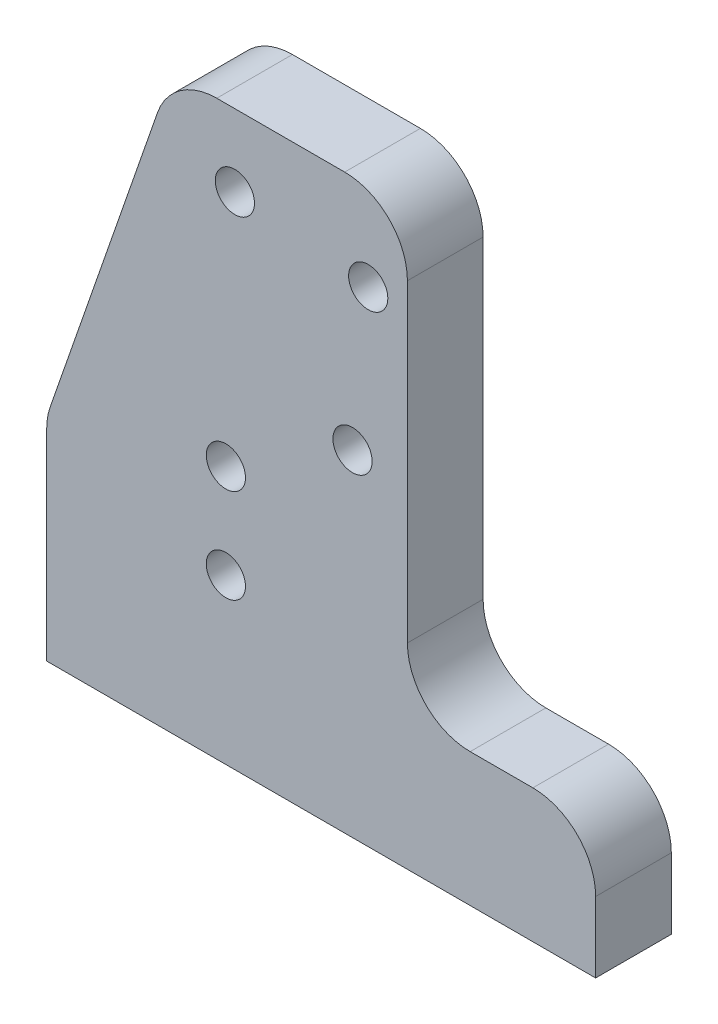
SolidWorks part; units mm, degrees
other "Markup1"
sketch "Sketch26" plane through (35, 0, 4.826) normal (0.2759, -0.8282, 0.4878) x (0.8301, -0.0505, -0.5553)
material "6061 Alloy"
ref_plane "Front" through (0, 0, 0) normal (0, 0, 1) x (1, 0, 0)
ref_plane "Top" through (0, 0, 0) normal (0, 1, 0) x (1, 0, 0)
ref_plane "Right" through (0, 0, 0) normal (1, 0, 0) x (0, 0, -1)
sketch "Sketch1" plane through (0, 0, 0) normal (0, 0, 1) x (1, 0, 0)
  line L0 (0, 0) -> (0, 13.5)
  line L9 (35, 0) -> (0, 0)
  line L15 (8, 36.5) -> (23, 36.5)
  line L16 (23, 36.5) -> (23, 8.5)
  line L17 (23, 8.5) -> (35, 8.5)
  line L18 (35, 8.5) -> (35, 0)
  line L22 (8, 36.5) -> (0, 13.5)
  dimension "D3" = 13.5
  dimension "D1" = 35
  dimension "D2" = 12
  dimension "D4" = 15
  dimension "D5" = 36.5
  dimension "D6" = 8.5
extrude "Boss-Extrude1" add sketch "Sketch1" along normal blind 4.826
hole_wizard "M3x0.5 Tapped Hole2" positions "Sketch13" profile "Sketch14" tap size "M3x0.5" standard "ANSI Metric" end condition through all
sketch "Sketch13" plane through (0, 0, 4.826) normal (0, 0, 1) x (1, 0, 0)
  line L3 (8, 36.5) -> (23, 36.5) construction
  point P5 (12, 31.9)
  dimension "D1" = 4.6
  dimension "D2" = 12
sketch "Sketch14" plane through (12, 31.9, 4.826) normal (1, 0, 0) x (0, -1, 0)
  line L0 (0, 0) -> (0, 4.826)
  line L1 (0, 4.826) -> (1.25, 4.826)
  line L2 (1.25, 4.826) -> (1.25, 0)
  line L5 (1.25, 0) -> (0, 0)
  line L11 (0, -6.35) -> (0, 107.95) construction
  dimension "Thru Tap Drill Dia." = 2.5
  dimension "Thru Tap Drill Depth" = 4.826
cosmetic thread "Hole Thread1" parameters "D2"=3
sketch "Sketch16" plane through (0, 0, 0) normal (0, -1, 0) x (1, 0, 0)
  line L0 (0, 4.826) -> (0, 0) construction
  line L3 (0, 2.413) -> (42.6944, 2.413) construction
  point P0 (28.73, 2.413)
  point P1 (16.73, 2.413)
  dimension "D1" = 16.73
  dimension "D2" = 12
hole_wizard "M3x0.5 Tapped Hole3" positions "Sketch17" profile "Sketch18" tap size "M3x0.5" standard "ANSI Metric"
sketch "Sketch17" plane through (0, 0, 0) normal (0, -1, 0) x (-1, 0, 0)
  point P0 (-16.73, -2.413)
  point P3 (-28.73, -2.413)
sketch "Sketch18" plane through (16.73, 0, 2.413) normal (1, 0, 0) x (0, 0, -1)
  line L0 (0, 0) -> (0, 5.7511)
  line L1 (0, 5.7511) -> (1.25, 5)
  line L2 (1.25, 5) -> (1.25, 0)
  line L5 (1.25, 0) -> (0, 0)
  line L10 (0, 5.7511) -> (-1.25, 5) construction
  line L11 (0, -6.35) -> (0, 107.95) construction
  dimension "Tap Drill Dia." = 2.5
  dimension "Tap Drill Depth" = 5
  dimension "Drill Angle" = 118
cosmetic thread "Hole Thread6" parameters "D1"=6, "D2"=3
cosmetic thread "Hole Thread7" parameters "D1"=6, "D2"=3
fillet "Fillet2" radius 4 5 edges at (35, 8.5, 2.413) (23, 8.5, 2.413) (23, 36.5, 2.413) (0, 13.5, 2.413) (8, 36.5, 2.413)
sketch "Sketch19" plane through (0, 0, 4.826) normal (0, 0, 1) x (1, 0, 0)
  circle A0 centre (19.5, 21.4) radius 1.4
  circle A1 centre (12, 31.9) radius 1.25 construction
  dimension "D3" = 2.8
  dimension "D1" = 10.5
  dimension "D2" = 7.5
sketch "Sketch23" plane through (0, 0, 4.826) normal (0, 0, 1) x (1, 0, 0)
  circle A0 centre (20.5, 30.9) radius 1.25
  circle A1 centre (12, 31.9) radius 1.25 construction
  dimension "D3" = 2.5
  dimension "D1" = 8.5
  dimension "D2" = 1
sketch "Sketch28" plane through (0, 0, 4.826) normal (0, 0, 1) x (1, 0, 0)
  circle A0 centre (11.425, 16.46) radius 1.4
  circle A1 centre (11.425, 10.46) radius 1.4
  circle A2 centre (12, 31.9) radius 1.25 construction
  dimension "D3" = 2.8
  dimension "D1" = 15.44
  dimension "D2" = 6
  dimension "D5" = 0.575
hole_wizard "M3x0.5 Tapped Hole4" positions "Sketch29" profile "Sketch30" tap size "M3x0.5" standard "ANSI Metric" end condition through all
sketch "Sketch29" plane through (0, 0, 4.826) normal (0, 0, 1) x (1, 0, 0)
  point P0 (19.5, 21.4)
  point P3 (20.5, 30.9)
sketch "Sketch30" plane through (19.5, 21.4, 4.826) normal (1, 0, 0) x (0, -1, 0)
  line L0 (0, 0) -> (0, 4.826)
  line L1 (0, 4.826) -> (1.25, 4.826)
  line L2 (1.25, 4.826) -> (1.25, 0)
  line L5 (1.25, 0) -> (0, 0)
  line L11 (0, -6.35) -> (0, 107.95) construction
  dimension "Thru Tap Drill Dia." = 2.5
  dimension "Thru Tap Drill Depth" = 4.826
cosmetic thread "Hole Thread2" parameters "D2"=3
cosmetic thread "Hole Thread3" parameters "D2"=3
hole_wizard "M3x0.5 Tapped Hole5" positions "Sketch33" profile "Sketch34" tap size "M3x0.5" standard "ANSI Metric" end condition through all
sketch "Sketch33" plane through (0, 0, 4.826) normal (0, 0, 1) x (1, 0, 0)
  point P0 (11.425, 16.46)
  point P3 (11.425, 10.46)
sketch "Sketch34" plane through (11.425, 16.46, 4.826) normal (1, 0, 0) x (0, -1, 0)
  line L0 (0, 0) -> (0, 4.826)
  line L1 (0, 4.826) -> (1.25, 4.826)
  line L2 (1.25, 4.826) -> (1.25, 0)
  line L5 (1.25, 0) -> (0, 0)
  line L11 (0, -6.35) -> (0, 107.95) construction
  dimension "Thru Tap Drill Dia." = 2.5
  dimension "Thru Tap Drill Depth" = 4.826
cosmetic thread "Hole Thread4" parameters "D2"=3
cosmetic thread "Hole Thread5" parameters "D2"=3
